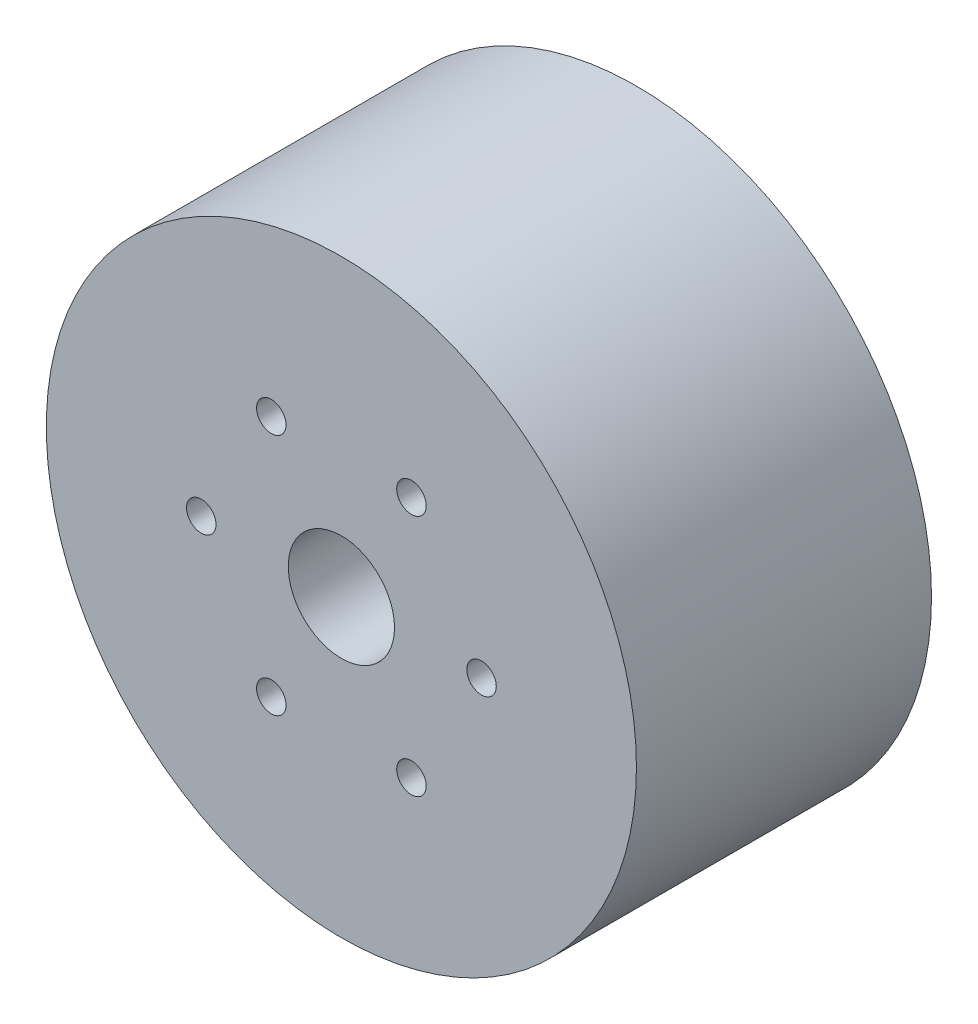
SolidWorks part; units mm, degrees
ref_plane "Спереди" through (0, 0, 0) normal (0, 0, 1) x (1, 0, 0)
ref_plane "Сверху" through (0, 0, 0) normal (0, 1, 0) x (1, 0, 0)
ref_plane "Справа" through (0, 0, 0) normal (1, 0, 0) x (0, 0, -1)
sketch "Эскиз1" plane through (0, 0, 0) normal (0, 0, 1) x (1, 0, 0)
  circle A0 centre (0, 0) radius 50
  circle A1 centre (0, 0) radius 9
  dimension "D1" = 100
  dimension "D2" = 18
extrude "Бобышка-Вытянуть1" add sketch "Эскиз1" along normal blind 50
sketch "Эскиз2" plane through (0, 0, 50) normal (0, 0, 1) x (1, 0, 0)
  circle A0 centre (23.75, 0) radius 2.5
  dimension "D1" = 5
  dimension "D2" = 23.75
extrude "Вырез-Вытянуть1" cut sketch "Эскиз2" against normal through all both and the other way through all
pattern_circular "Круговой массив1" count 6 every 60 about axis through (0, 0, 0) along (0, 0, 1) of "Вырез-Вытянуть1"
